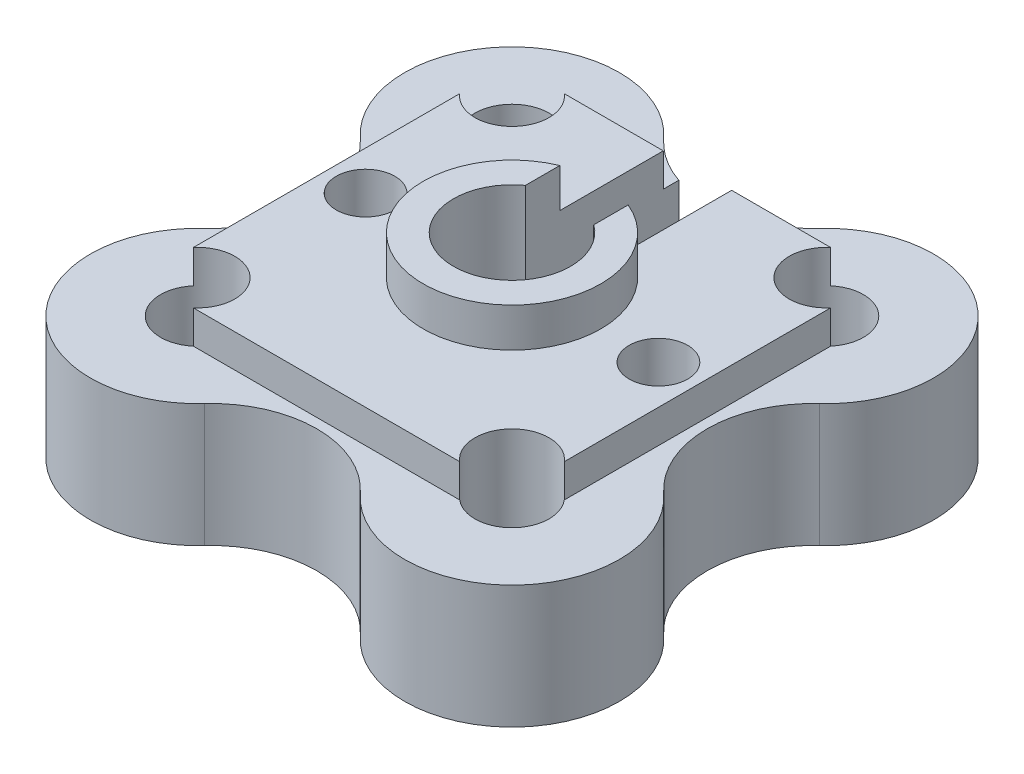
SolidWorks part; units mm, degrees
material "POM Acetal Copolymer"
ref_plane "Front Plane" through (0, 0, 0) normal (0, 0, 1) x (1, 0, 0)
ref_plane "Top Plane" through (0, 0, 0) normal (0, 1, 0) x (1, 0, 0)
ref_plane "Right Plane" through (0, 0, 0) normal (1, 0, 0) x (0, 0, -1)
sketch "Sketch1" plane through (0, 0, 0) normal (0, 1, 0) x (1, 0, 0)
  line L0 (-8.05, 8.05) -> (8.05, 8.05) construction
  line L2 (8.05, -8.05) -> (8.05, -6.15) construction
  line L4 (8.05, -8.05) -> (8.05, 8.05) construction
  line L5 (8.05, 8.05) -> (8.05, 0) construction
  line L6 (8.05, -8.05) -> (-8.05, -8.05) construction
  line L7 (0, 0) -> (8.05, 8.05) construction
  line L9 (0, 0) -> (8.05, -8.05) construction
  line L10 (-8.05, 8.05) -> (0, 0) construction
  line L11 (-8.05, -8.05) -> (0, 0) construction
  line L13 (0, -1000) -> (0, 49000) construction
  line L14 (-1000, 0) -> (49000, 0) construction
  line L15 (8.05, -6.15) -> (8.05, -8.05) construction
  line L16 (-8.05, 8.05) -> (-8.05, -8.05) construction
  line L17 (10, -998.4709) -> (10, 49001.5291) construction
  line L18 (-10, -998.768) -> (-10, 49001.232) construction
  line L19 (-1000, 10) -> (49000, 10) construction
  line L20 (-1000.9125, -10) -> (48999.0875, -10) construction
  circle A0 centre (-8.05, 8.05) radius 1.9 construction
  circle A1 centre (-8.05, -8.05) radius 1.9 construction
  circle A2 centre (8.05, -8.05) radius 1.9 construction
  circle A3 centre (8.05, 8.05) radius 1.9 construction
  circle A4 centre (0, 0) radius 3 construction
  arc A5 (-3.9889, -11.7591) -> (-11.7591, -3.9889) centre (-8.05, -8.05) cw
  arc A6 (-3.9889, -11.7591) -> (3.9889, -11.7591) centre (0, -15.4021) cw
  circle A7 centre (-7.5, 0) radius 1.5
  circle A8 centre (7.5, 0) radius 1.5
  arc A9 (-11.7591, -3.9889) -> (-11.7591, 3.9889) centre (-15.4021, 0) ccw
  arc A10 (11.7591, -3.9889) -> (3.9889, -11.7591) centre (8.05, -8.05) cw
  arc A11 (-3.9889, 11.7591) -> (-11.7591, 3.9889) centre (-8.05, 8.05) ccw
  arc A13 (11.7591, 3.9889) -> (11.7591, -3.9889) centre (15.4021, 0) ccw
  circle A14 centre (8.05, -8.05) radius 1.9 construction
  arc A15 (-3.9889, 11.7591) -> (3.9889, 11.7591) centre (0, 15.4021) ccw
  circle A16 centre (8.05, 8.05) radius 1.9 construction
  arc A23 (11.7591, 3.9889) -> (3.9889, 11.7591) centre (8.05, 8.05) ccw
  point P59 (13.55, -21.5)
  point P62 (-13.55, -21.5)
  dimension "D1" = 3.8
  dimension "D7" = 6
  dimension "D8" = 5.5
  dimension "D11" = 15
  dimension "D14" = 20
  dimension "D5" = 3
  dimension "D4" = 5.5
  dimension "D2" = 16.1
  dimension "D15" = 20
extrude "Boss-Extrude1" add sketch "Sketch1" along normal blind 6.3
sketch "Sketch3" plane through (0, 6.3, 0) normal (0, 1, 0) x (1, 0, 0)
  circle A2 centre (-8.05, -8.05) radius 1.9 construction
  circle A3 centre (-8.05, 8.05) radius 1.9 construction
  circle A4 centre (8.05, 8.05) radius 1.9 construction
  circle A5 centre (8.05, -8.05) radius 1.9 construction
  circle A7 centre (-8.05, 8.05) radius 1.9
  circle A8 centre (8.05, 8.05) radius 1.9
  circle A9 centre (8.05, -8.05) radius 1.9
  circle A10 centre (-8.05, -8.05) radius 1.9
extrude "Cut-Extrude3" cut sketch "Sketch3" against normal offset from surface (5.3 mm away) 1 up to face at (-7.5, 0, 1.5)
sketch "Sketch5" plane through (0, 6.3, 0) normal (0, 1, 0) x (1, 0, 0)
  line L0 (-9.5, 6.8222) -> (-9.5, -6.8222)
  line L1 (-6.8222, -9.5) -> (6.8222, -9.5)
  line L2 (9.5, -6.8222) -> (9.5, 6.8222)
  line L3 (6.8222, 9.5) -> (-6.8222, 9.5)
  line L4 (0, -1000) -> (0, 49000) construction
  line L5 (-1000, 0) -> (49000, 0) construction
  line L6 (-201000, 0) -> (249000, 0) construction
  line L7 (0, -201000) -> (0, 249000) construction
  arc A0 (-6.8222, -9.5) -> (-9.5, -6.8222) centre (-8.05, -8.05) ccw
  arc A1 (-9.5, 6.8222) -> (-6.8222, 9.5) centre (-8.05, 8.05) ccw
  arc A2 (9.5, -6.8222) -> (6.8222, -9.5) centre (8.05, -8.05) ccw
  arc A3 (6.8222, 9.5) -> (9.5, 6.8222) centre (8.05, 8.05) ccw
  circle A4 centre (-8.05, -8.05) radius 1.9 construction
  circle A5 centre (-8.05, 8.05) radius 1.9 construction
  circle A6 centre (8.05, -8.05) radius 1.9 construction
  circle A7 centre (8.05, 8.05) radius 1.9 construction
  dimension "D1" = 19
  dimension "D2" = 19
extrude "Boss-Extrude2" add sketch "Sketch5" along normal blind 1.7
sketch "Sketch7" plane through (0, 8, 0) normal (0, 1, 0) x (1, 0, 0)
  circle A0 centre (0, 0) radius 4.55
  dimension "D1" = 9.1
extrude "Boss-Extrude3" add sketch "Sketch7" along normal blind 2
sketch "Sketch6" plane through (0, 0, 0) normal (0, 1, 0) x (1, 0, 0)
  circle A0 centre (-7.5, 0) radius 1.5
  circle A1 centre (0, 0) radius 3
  circle A2 centre (7.5, 0) radius 1.5
  circle A3 centre (-7.5, 0) radius 1.5 construction
  circle A5 centre (7.5, 0) radius 1.5 construction
  dimension "D1" = 6
extrude "Cut-Extrude4" cut sketch "Sketch6" along normal through all
sketch "Sketch8" plane through (0, 10, 0) normal (0, 1, 0) x (1, 0, 0)
  line L1 (0, -1000) -> (0, 49000) construction
  line L2 (0, 0) -> (0, 12) construction
  line L3 (-1.75, 0) -> (-1.75, 12)
  line L4 (1.75, 0) -> (1.75, 12)
  arc A0 (-1.75, 0) -> (1.75, 0) centre (0, 0) ccw
  arc A1 (1.75, 12) -> (-1.75, 12) centre (0, 12) ccw
  point P8 (0, 6)
  dimension "D1" = 3.5
  dimension "D2" = 12
extrude "Cut-Extrude5" cut sketch "Sketch8" against normal through all
sketch "Sketch9" plane through (0, 0, 0) normal (0, -1, 0) x (1, 0, 0)
  line L0 (-1.75, -10.2913) -> (-1.75, -2.4367) construction
  line L1 (-1.75, -2.4367) -> (-1.75, 0)
  line L2 (1.75, -2.4367) -> (1.75, 0)
  line L4 (-1.75, 0) -> (-1.75, -12) construction
  line L5 (1.75, 0) -> (1.75, -12) construction
  arc A1 (1.75, 0) -> (-1.75, 0) centre (0, 0) ccw
  arc A6 (1.75, 0) -> (-1.75, 0) centre (0, 0) ccw construction
  arc A7 (1.75, -2.4367) -> (-1.75, -2.4367) centre (0, 0) ccw
  arc A8 (1.75, -2.4367) -> (-1.75, -2.4367) centre (0, 0) ccw construction
  dimension "D1" = 3.5
extrude "Boss-Extrude4" add sketch "Sketch9" against normal offset from surface (3.65 mm away) 6.35 up to face at (0, 10, 0.2283)
